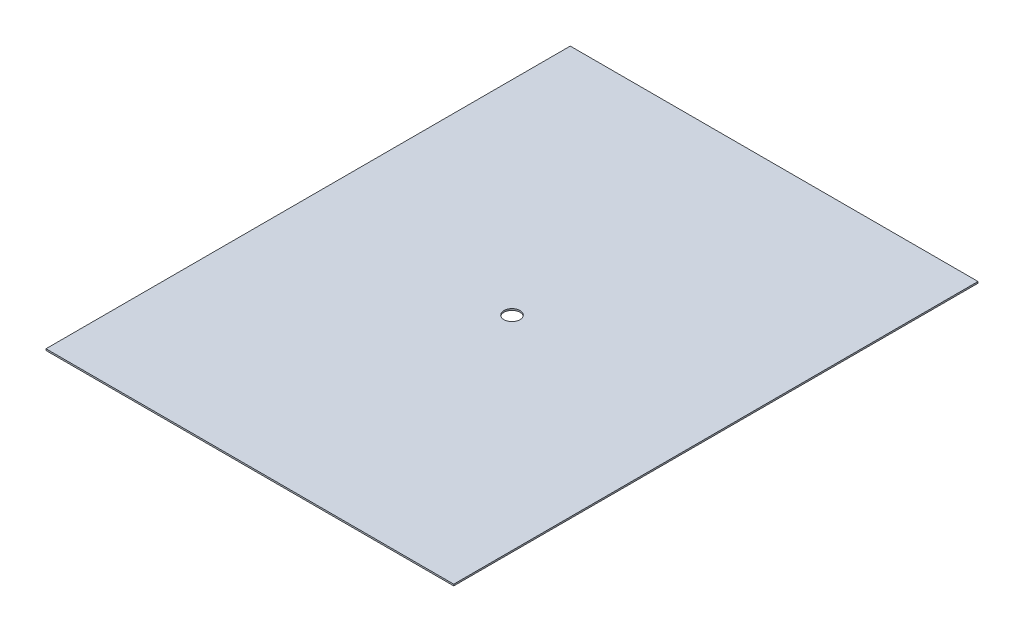
SolidWorks part; units mm, degrees
ref_plane "Front Plane" through (0, 0, 0) normal (0, 0, 1) x (1, 0, 0)
ref_plane "Top Plane" through (0, 0, 0) normal (0, 1, 0) x (1, 0, 0)
ref_plane "Right Plane" through (0, 0, 0) normal (1, 0, 0) x (0, 0, -1)
sketch "Sketch1" plane through (0, 0, 0) normal (0, 1, 0) x (1, 0, 0)
  line L1 (100.0125, 128.5875) -> (-100.0125, 128.5875)
  line L2 (100.0125, 128.5875) -> (100.0125, -128.5875)
  line L3 (100.0125, -128.5875) -> (-100.0125, -128.5875)
  line L4 (-100.0125, 128.5875) -> (-100.0125, -128.5875)
  line L5 (100.0125, 128.5875) -> (-100.0125, -128.5875) construction
  line L6 (100.0125, -128.5875) -> (-100.0125, 128.5875) construction
  circle A0 centre (0, 0) radius 3.9116
  point P0 (0, 0)
  dimension "D3" = 7.8232
  dimension "D1" = 200.025
  dimension "D2" = 257.175
extrude "Boss-Extrude1" add sketch "Sketch1" along normal blind 0.762
